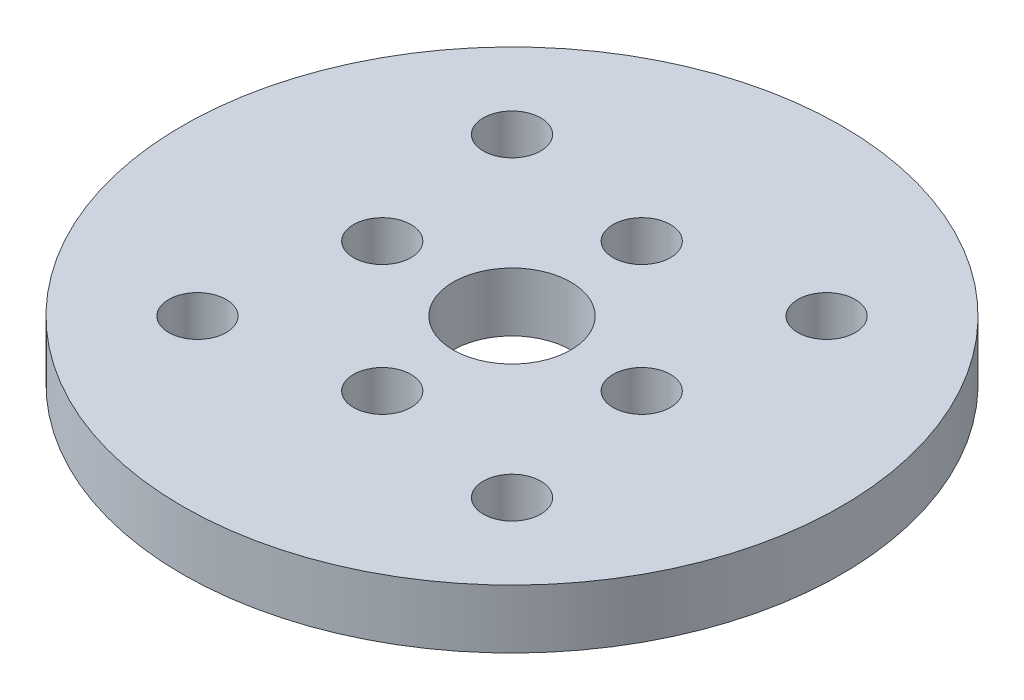
SolidWorks part; units mm, degrees
ref_plane "Front Plane" through (0, 0, 0) normal (0, 0, 1) x (1, 0, 0)
ref_plane "Top Plane" through (0, 0, 0) normal (0, 1, 0) x (1, 0, 0)
ref_plane "Right Plane" through (0, 0, 0) normal (1, 0, 0) x (0, 0, -1)
sketch "Sketch1" plane through (0, 0, 0) normal (0, 0, 1) x (1, 0, 0)
  line L0 (4.572, 0) -> (4.572, 1.905)
  line L1 (4.572, 1.905) -> (9.906, 1.905)
  line L2 (9.906, 1.905) -> (9.906, 4.445)
  line L3 (9.906, 4.445) -> (1.397, 4.445)
  line L4 (1.397, 4.445) -> (1.397, 2.54)
  line L5 (1.397, 2.54) -> (3.175, 2.54)
  line L6 (3.175, 2.54) -> (3.175, 0)
  line L7 (3.175, 0) -> (4.572, 0)
  line L8 (0, 0) -> (0, 6.858) construction
  dimension "D1" = 2.54
  dimension "D2" = 1.905
  dimension "D3" = 2.794
  dimension "D4" = 3.175
  dimension "D5" = 9.144
  dimension "D6" = 19.812
  dimension "D7" = 1.905
revolve "Revolve1" add sketch "Sketch1" angle 360 about L8
sketch "Sketch2" plane through (0, 4.445, 0) normal (0, 1, 0) x (1, 0, 0)
  line L0 (0, 0) -> (0, 9.906) construction
  circle A0 centre (0, 0) radius 9.906 construction
  circle A1 centre (0, 7) radius 1.27
  circle A2 centre (7, 0) radius 1.27
  circle A3 centre (0, -7) radius 1.27
  circle A4 centre (-7, 0) radius 1.27
  point P17 (0, 0)
  dimension "D1" = 2.54
  dimension "D3" = 14
  dimension "D2" = 4
extrude "Cut-Extrude1" cut sketch "Sketch2" against normal through all
sketch "Sketch3" plane through (0, 4.445, 0) normal (0, 1, 0) x (1, 0, 0)
  line L0 (0, 0) -> (-8.4853, 8.4853) construction
  line L1 (0, 0) -> (-7, 0) construction
  circle A0 centre (7, 0) radius 1.27 construction
  circle A1 centre (0, 0) radius 3.175
  circle A3 centre (0, -7) radius 1.27 construction
  circle A5 centre (0, 7) radius 1.27 construction
  circle A6 centre (-7, 0) radius 1.27 construction
  circle A7 centre (7, 0) radius 1.27 construction
  circle A8 centre (0, -7) radius 1.27 construction
  circle A10 centre (0, 7) radius 1.27 construction
  circle A11 centre (-7, 0) radius 1.27 construction
  circle A12 centre (-8.4853, 8.4853) radius 1.55
  circle A13 centre (0, 7) radius 1.55
  circle A14 centre (7, 0) radius 1.55
  circle A15 centre (0, -7) radius 1.55
  circle A16 centre (-7, 0) radius 1.55
  circle A17 centre (8.4853, 8.4853) radius 1.55
  circle A18 centre (8.4853, -8.4853) radius 1.55
  circle A19 centre (-8.4853, -8.4853) radius 1.55
  circle A20 centre (0, 0) radius 17.78
  point P30 (0, 0)
  dimension "D1" = 6.35
  dimension "D2" = 3.1
  dimension "D6" = 3.1
  dimension "D7" = 35.56
  dimension "D4" = 45
  dimension "D5" = 12
  dimension "D3" = 4
extrude "Boss-Extrude1" add sketch "Sketch3" along normal blind 3.175 separate body
delete or keep bodies "Body-Delete/Keep 1" type keep bodies bodies 103
